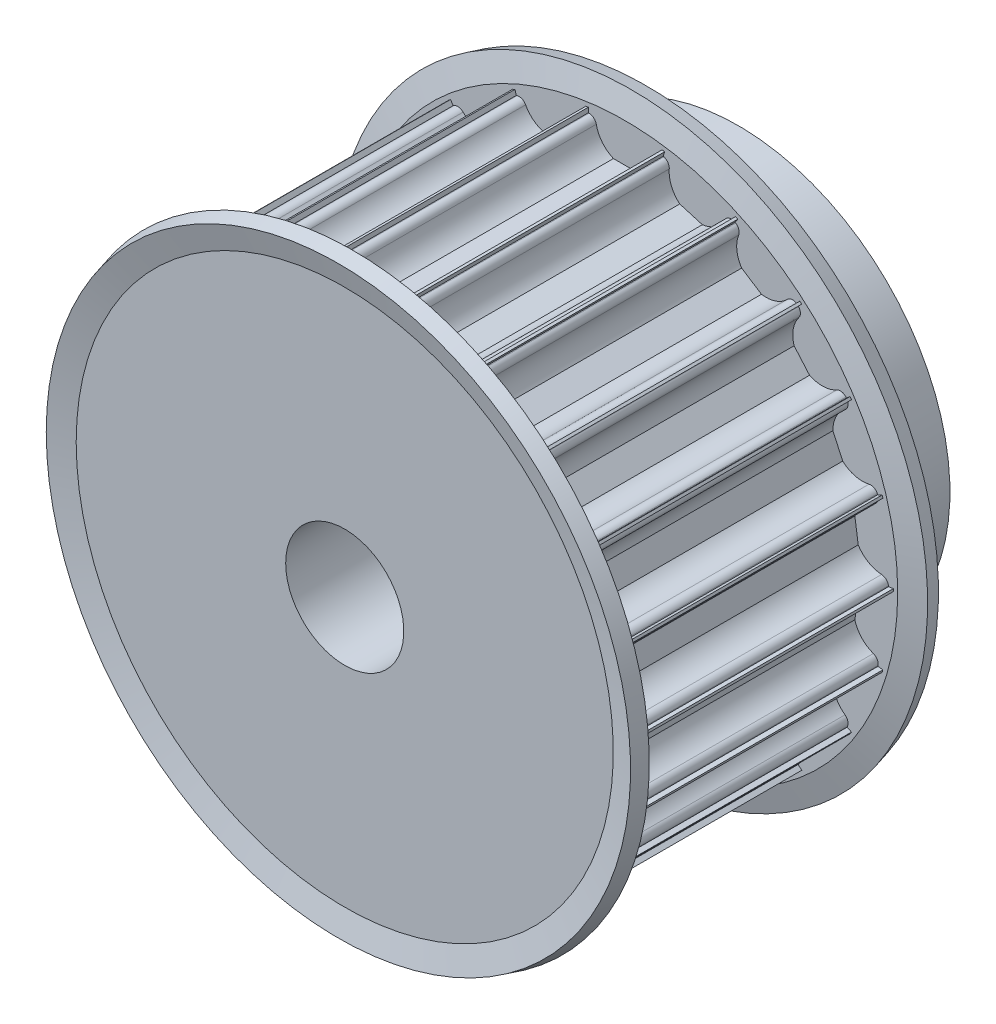
SolidWorks part; units mm, degrees
ref_plane "Front Plane" through (0, 0, 0) normal (0, 0, 1) x (1, 0, 0)
ref_plane "Top Plane" through (0, 0, 0) normal (0, 1, 0) x (1, 0, 0)
ref_plane "Right Plane" through (0, 0, 0) normal (1, 0, 0) x (0, 0, -1)
ref_axis "Axis1" through (0, 0, -88.99) along (0, 0, 1)
sketch "Sketch1" plane through (0, 0, 0) normal (1, 0, 0) x (0, 0, -1)
  line L0 (0, 6) -> (0, 27.25)
  line L1 (0, 27.25) -> (30, 27.25)
  line L2 (30, 27.25) -> (30, 21.5)
  line L3 (30, 21.5) -> (40, 21.5)
  line L4 (40, 21.5) -> (40, 6)
  line L5 (40, 6) -> (0, 6)
  dimension "D1" = 6
  dimension "D2" = 21.25
  dimension "D3" = 30
  dimension "D4" = 10
  dimension "D5" = 15.5
revolve "Revolve1" add sketch "Sketch1" angle 360 about axis through (0, 0, -88.99) along (0, 0, 1)
sketch "Sketch2" plane through (0, 0, 0) normal (0, 0, 1) x (1, 0, 0)
  line L0 (3.6742, 26.5) -> (3.75, 26.5)
  line L1 (-3.75, 28.5) -> (3.75, 28.5)
  line L2 (-3.75, 28.5) -> (-3.75, 26.5)
  line L3 (-3.75, 26.5) -> (-3.6742, 26.5)
  line L4 (3.75, 28.5) -> (3.75, 26.5)
  line L5 (-1.199, 23.75) -> (1.199, 23.75)
  arc A0 (-2.9394, 25.9) -> (-1.199, 23.75) centre (0, 26.5) ccw
  arc A1 (-2.9394, 25.9) -> (-3.6742, 26.5) centre (-3.6742, 25.75) ccw
  arc A2 (2.9394, 25.9) -> (3.6742, 26.5) centre (3.6742, 25.75) cw
  arc A3 (1.199, 23.75) -> (2.9394, 25.9) centre (0, 26.5) ccw
  dimension "D1" = 3
  dimension "D5" = 0.75
  dimension "D6" = 0.75
  dimension "D2" = 2
  dimension "D3" = 7.5
  dimension "D4" = 26.5
  dimension "D7" = 2.75
extrude "Cut-Extrude1" cut sketch "Sketch2" against normal through all
pattern_circular "CirPattern1" count 22 over 360 about axis through (0, 0, 0) along (0, 0, 1) of "Cut-Extrude1"
sketch "Sketch3" plane through (0, 0, 0) normal (1, 0, 0) x (0, 0, -1)
  line L0 (0, 26.9907) -> (30, 26.9907) construction
  line L1 (0, 27.6907) -> (1.5, 27.6907) construction
  line L2 (0, 27.6907) -> (0, 22.6907)
  line L3 (0, 22.6907) -> (1.5, 22.6907)
  line L4 (1.5, 27.6907) -> (1.5, 22.6907)
  line L5 (1.5, 27.6907) -> (0, 27.2888) construction
  line L6 (1.5, 27.6907) -> (0.8569, 30.0907)
  line L7 (0, 27.2888) -> (-0.6431, 29.6888)
  line L8 (0.8569, 30.0907) -> (-0.6431, 29.6888)
  line L9 (15, 26.9539) -> (15, -38.6245) construction
  line L10 (30, 26.9539) -> (0, 26.9539) construction
  line L11 (0, 24.2797) -> (0, 23.3776) construction
  line L12 (28.5, 27.6907) -> (30, 27.2888) construction
  line L13 (30, 27.6907) -> (28.5, 27.6907) construction
  line L14 (29.1431, 30.0907) -> (30.6431, 29.6888)
  line L15 (30, 27.2888) -> (30.6431, 29.6888)
  line L16 (28.5, 27.6907) -> (29.1431, 30.0907)
  line L17 (28.5, 27.6907) -> (28.5, 22.6907)
  line L18 (30, 22.6907) -> (28.5, 22.6907)
  line L19 (30, 27.6907) -> (30, 22.6907)
  dimension "D1" = 1.5
  dimension "D2" = 5
  dimension "D3" = 1.5
  dimension "D4" = 165
  dimension "D5" = 2.4
  dimension "D6" = 0.7
revolve "Revolve2" add sketch "Sketch3" angle 360 about axis through (0, 0, -88.99) along (0, 0, 1)
